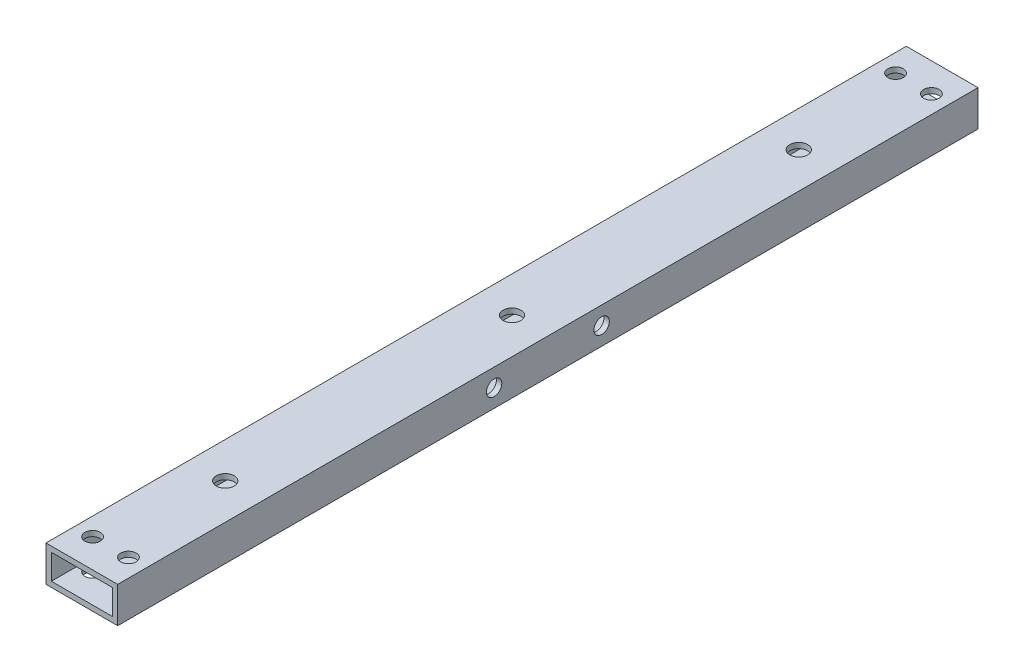
SolidWorks part; units mm, degrees
material "5052-H34"
ref_plane "正面" through (0, 0, 0) normal (0, 0, 1) x (1, 0, 0)
ref_plane "平面" through (0, 0, 0) normal (0, 1, 0) x (1, 0, 0)
ref_plane "右側面" through (0, 0, 0) normal (1, 0, 0) x (0, 0, -1)
sketch "ｽｹｯﾁ1" plane through (0, 0, 0) normal (0, 0, 1) x (1, 0, 0)
  line L1 (-10, 5) -> (10, 5)
  line L2 (-10, 5) -> (-10, -5)
  line L3 (-10, -5) -> (10, -5)
  line L4 (10, 5) -> (10, -5)
  line L5 (-10, 5) -> (10, -5) construction
  line L6 (-10, -5) -> (10, 5) construction
  point P0 (0, 0)
  dimension "D1" = 20
  dimension "D2" = 10
extrude "押し出し-薄板1" add sketch "ｽｹｯﾁ1" along normal blind 240 thin
sketch "ｽｹｯﾁ2" plane through (0, 5, 0) normal (0, 1, 0) x (1, 0, 0)
  line L0 (-10, -120) -> (10, -120) construction
  line L1 (-10, -240) -> (-10, 0) construction
  line L2 (10, -240) -> (10, 0) construction
  line L3 (0, -240) -> (0, -232) construction
  line L4 (10, -240) -> (-10, -240) construction
  line L5 (0, -232) -> (5, -232) construction
  line L6 (0, -120) -> (0, -40) construction
  circle A0 centre (5, -232) radius 2.15
  circle A1 centre (-5, -232) radius 2.15
  circle A2 centre (5, -8) radius 2.15
  circle A3 centre (-5, -8) radius 2.15
  circle A4 centre (0, -40) radius 2.5
  circle A5 centre (0, -200) radius 2.5
  circle A6 centre (0, -120) radius 2.5
  dimension "D1" = 4.3
  dimension "D4" = 5
  dimension "D6" = 5
  dimension "D2" = 8
  dimension "D3" = 10
  dimension "D5" = 160
extrude "ｶｯﾄ - 押し出し1" cut sketch "ｽｹｯﾁ2" against normal through all
sketch "ｽｹｯﾁ3" plane through (10, 0, 0) normal (1, 0, 0) x (0, 0, -1)
  line L0 (-120, 5) -> (-120, -5) construction
  line L1 (-240, 5) -> (0, 5) construction
  line L2 (-240, -5) -> (0, -5) construction
  line L3 (-120, 0) -> (-105, 0) construction
  circle A0 centre (-105, 0) radius 2.15
  circle A1 centre (-135, 0) radius 2.15
  dimension "D2" = 4.3
  dimension "D1" = 30
extrude "ｶｯﾄ - 押し出し2" cut sketch "ｽｹｯﾁ3" against normal through all
